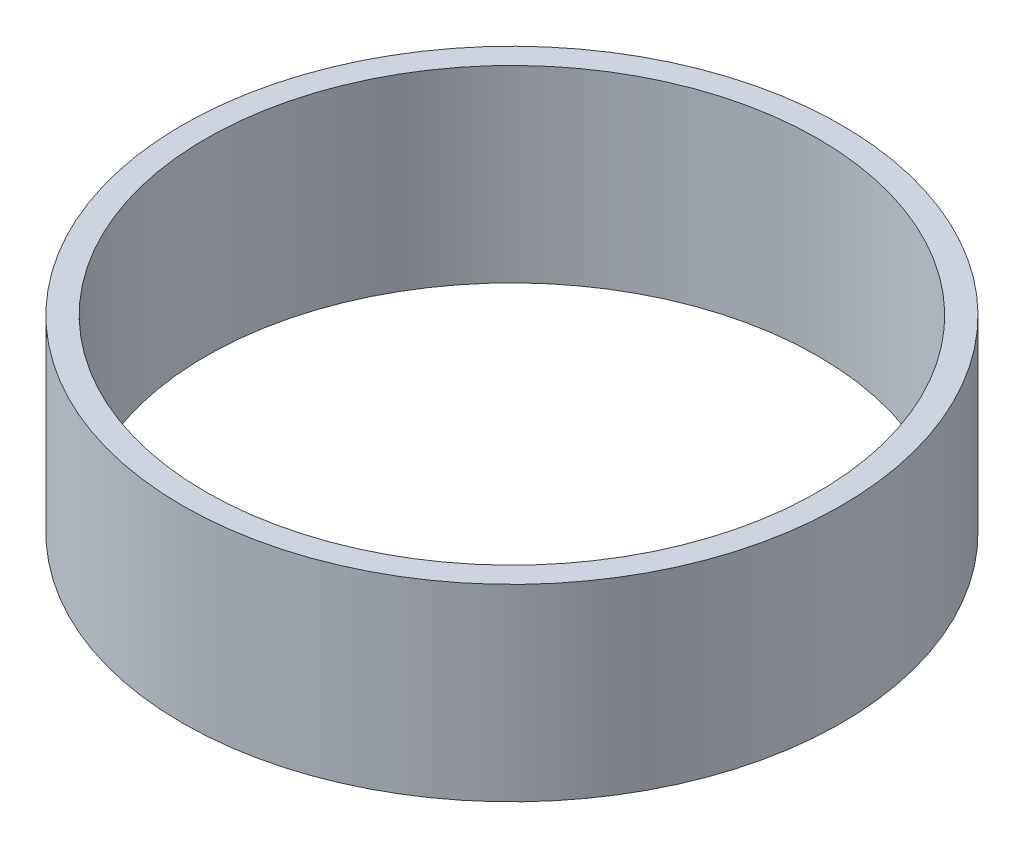
SolidWorks part; units mm, degrees
ref_plane "Front Plane" through (0, 0, 0) normal (0, 0, 1) x (1, 0, 0)
ref_plane "Top Plane" through (0, 0, 0) normal (0, 1, 0) x (1, 0, 0)
ref_plane "Right Plane" through (0, 0, 0) normal (1, 0, 0) x (0, 0, -1)
sketch "Sketch1" plane through (0, 0, 0) normal (0, 1, 0) x (1, 0, 0)
  circle A0 centre (0, 0) radius 6.5
  circle A1 centre (0, 0) radius 7
  dimension "D1" = 13
  dimension "D2" = 14
extrude "Boss-Extrude1" add sketch "Sketch1" along normal blind 4
